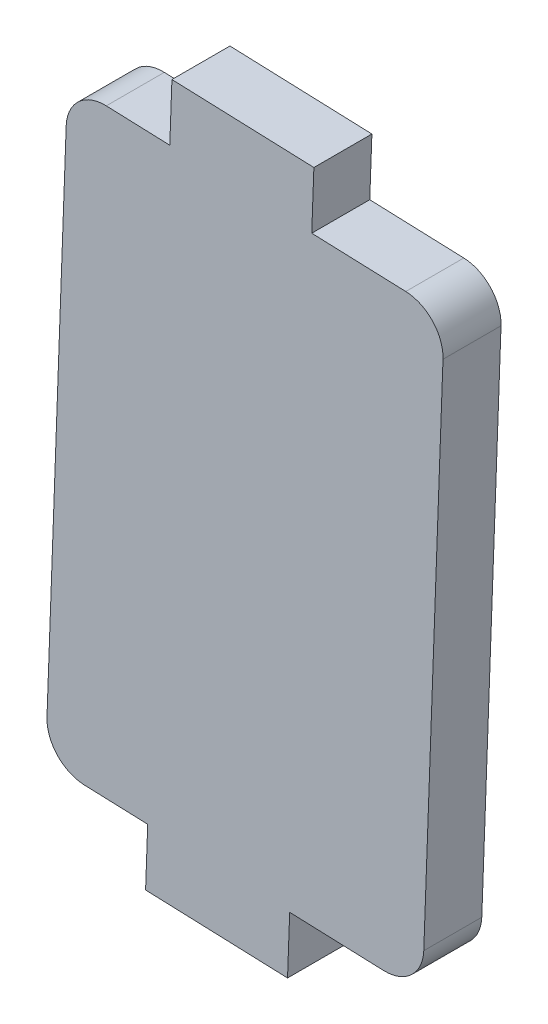
SolidWorks part; units mm, degrees
ref_plane "Front" through (0, 0, 0) normal (0, 0, 1) x (1, 0, 0)
ref_plane "Top" through (0, 0, 0) normal (0, 1, 0) x (1, 0, 0)
ref_plane "Right" through (0, 0, 0) normal (1, 0, 0) x (0, 0, -1)
sketch "Sketch1" plane through (0, 0, 0) normal (0, 0, 1) x (1, 0, 0)
  line L0 (701.5624, 484.6423) -> (701.6729, 487.6402)
  line L1 (708.9024, 484.3719) -> (709.0129, 487.3699)
  line L2 (708.9024, 484.3719) -> (701.5624, 484.6423)
  line L3 (702.8139, 518.6192) -> (702.9243, 521.6172)
  line L4 (710.1539, 518.3489) -> (710.2643, 521.3468)
  line L5 (713.8746, 487.1908) -> (709.0129, 487.3699)
  line L6 (715.0156, 518.1698) -> (710.1539, 518.3489)
  line L7 (697.4581, 516.8151) -> (696.4643, 489.8334)
  line L8 (701.6729, 487.6402) -> (698.3893, 487.7612)
  line L9 (702.8139, 518.6192) -> (699.5303, 518.7402)
  line L10 (716.9407, 516.0975) -> (715.9469, 489.1158)
  line L11 (710.2643, 521.3468) -> (702.9243, 521.6172)
  arc A0 (697.4581, 516.8151) -> (699.5303, 518.7402) centre (699.4567, 516.7415) cw
  arc A1 (716.9407, 516.0975) -> (715.0156, 518.1698) centre (714.942, 516.1712) ccw
  arc A2 (696.4643, 489.8334) -> (698.3893, 487.7612) centre (698.4629, 489.7598) ccw
  arc A3 (715.9469, 489.1158) -> (713.8746, 487.1908) centre (713.9482, 489.1895) cw
  dimension "D3" = 2
  dimension "D1" = 7.34
  dimension "D2" = 7.34
extrude "Base-Extrude" add sketch "Sketch1" along normal blind 3
